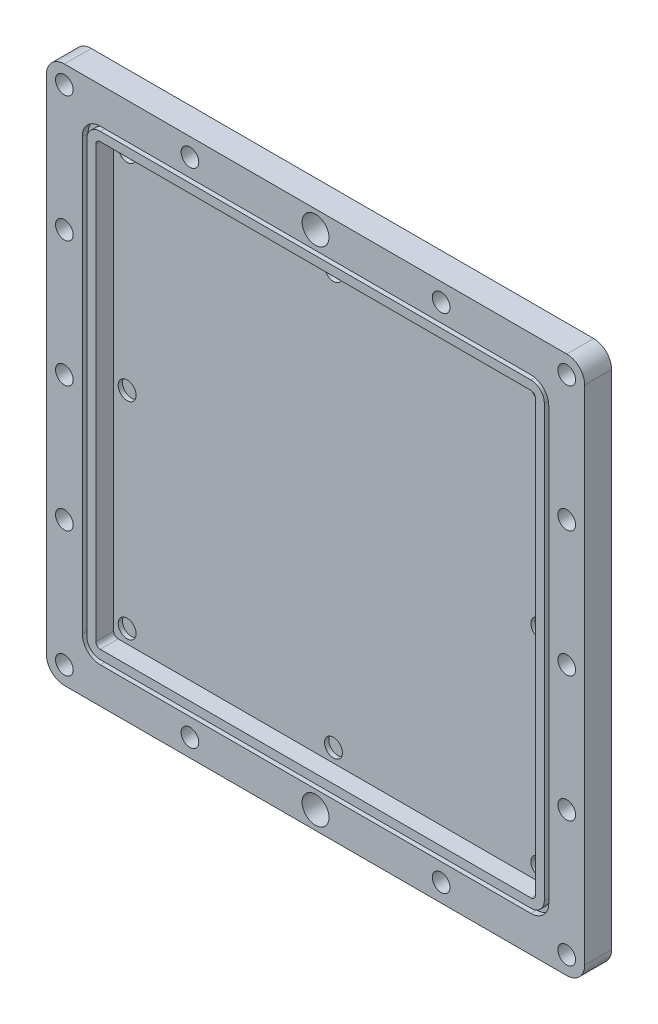
SolidWorks part; units mm, degrees
ref_plane "Front Plane" through (0, 0, 0) normal (0, 0, 1) x (1, 0, 0)
ref_plane "Top Plane" through (0, 0, 0) normal (0, 1, 0) x (1, 0, 0)
ref_plane "Right Plane" through (0, 0, 0) normal (1, 0, 0) x (0, 0, -1)
sketch "Sketch1" plane through (0, 0, 0) normal (0, 0, 1) x (1, 0, 0)
  line L1 (0, 0) -> (190.5, 0)
  line L2 (0, 0) -> (0, 190.5)
  line L3 (0, 190.5) -> (190.5, 190.5)
  line L4 (190.5, 0) -> (190.5, 190.5)
  dimension "D1" = 190.5
  dimension "D2" = 190.5
extrude "Boss-Extrude1" add sketch "Sketch1" along normal blind 9.525
sketch "Sketch4" plane through (0, 0, 9.525) normal (0, 0, 1) x (1, 0, 0)
  line L3 (0, 190.5) -> (0, 0) construction
  line L4 (6.35, 184.15) -> (184.15, 184.15) construction
  line L5 (6.35, 184.15) -> (6.35, 6.35) construction
  line L6 (6.35, 6.35) -> (184.15, 6.35) construction
  line L7 (184.15, 184.15) -> (184.15, 6.35) construction
  line L8 (190.5, 190.5) -> (0, 190.5) construction
  line L9 (190.5, 0) -> (190.5, 190.5) construction
  line L10 (0, 0) -> (190.5, 0) construction
  circle A0 centre (6.35, 6.35) radius 3.1242
  circle A1 centre (6.35, 184.15) radius 3.1242
  circle A2 centre (184.15, 184.15) radius 3.1242
  circle A3 centre (184.15, 6.35) radius 3.1242
  dimension "D5" = 6.2484
  dimension "D1" = 6.35
  dimension "D2" = 6.35
  dimension "D3" = 6.35
  dimension "D4" = 6.35
extrude "Cut-Extrude1" cut sketch "Sketch4" against normal through all
sketch "Sketch5" plane through (0, 0, 9.525) normal (0, 0, 1) x (1, 0, 0)
  line L0 (0, 190.5) -> (0, 0) construction
  line L1 (19.05, 177.8) -> (171.45, 177.8)
  line L2 (12.7, 171.45) -> (12.7, 19.05)
  line L3 (19.05, 12.7) -> (171.45, 12.7)
  line L4 (177.8, 171.45) -> (177.8, 19.05)
  line L5 (190.5, 190.5) -> (0, 190.5) construction
  line L6 (190.5, 0) -> (190.5, 190.5) construction
  line L7 (0, 0) -> (190.5, 0) construction
  line L8 (19.05, 14.2875) -> (171.45, 14.2875)
  line L9 (14.2875, 171.45) -> (14.2875, 19.05)
  line L10 (19.05, 176.2125) -> (171.45, 176.2125)
  line L11 (176.2125, 171.45) -> (176.2125, 19.05)
  arc A0 (171.45, 12.7) -> (177.8, 19.05) centre (171.45, 19.05) ccw
  arc A1 (12.7, 19.05) -> (19.05, 12.7) centre (19.05, 19.05) ccw
  arc A2 (171.45, 177.8) -> (177.8, 171.45) centre (171.45, 171.45) cw
  arc A3 (19.05, 177.8) -> (12.7, 171.45) centre (19.05, 171.45) ccw
  arc A4 (14.2875, 19.05) -> (19.05, 14.2875) centre (19.05, 19.05) ccw
  arc A5 (19.05, 176.2125) -> (14.2875, 171.45) centre (19.05, 171.45) ccw
  arc A6 (171.45, 176.2125) -> (176.2125, 171.45) centre (171.45, 171.45) cw
  arc A7 (171.45, 14.2875) -> (176.2125, 19.05) centre (171.45, 19.05) ccw
  dimension "D5" = 6.35
  dimension "D1" = 12.7
  dimension "D2" = 12.7
  dimension "D3" = 12.7
  dimension "D4" = 12.7
  dimension "D6" = 1.5875
  dimension "D7" = 1.5875
extrude "Cut-Extrude2" cut sketch "Sketch5" against normal blind 2.032 contours L1 A3 L2 A1 L3 A0 L4 A2 A7 L8 A4 L9 A5 L10 A6 L11
sketch "Sketch6" plane through (0, 0, 9.525) normal (0, 0, 1) x (1, 0, 0)
  line L8 (173.0375, 19.05) -> (173.0375, 171.45)
  line L9 (171.45, 173.0375) -> (19.05, 173.0375)
  line L10 (17.4625, 171.45) -> (17.4625, 19.05)
  line L11 (19.05, 17.4625) -> (171.45, 17.4625)
  line L12 (173.0375, 19.05) -> (173.0375, 171.45)
  line L13 (171.45, 173.0375) -> (19.05, 173.0375)
  line L14 (17.4625, 171.45) -> (17.4625, 19.05)
  line L15 (19.05, 17.4625) -> (171.45, 17.4625)
  arc A8 (171.45, 17.4625) -> (173.0375, 19.05) centre (171.45, 19.05) ccw
  arc A9 (173.0375, 171.45) -> (171.45, 173.0375) centre (171.45, 171.45) ccw
  arc A10 (19.05, 173.0375) -> (17.4625, 171.45) centre (19.05, 171.45) ccw
  arc A11 (17.4625, 19.05) -> (19.05, 17.4625) centre (19.05, 19.05) ccw
  arc A12 (171.45, 17.4625) -> (173.0375, 19.05) centre (171.45, 19.05) ccw
  arc A13 (173.0375, 171.45) -> (171.45, 173.0375) centre (171.45, 171.45) ccw
  arc A14 (19.05, 173.0375) -> (17.4625, 171.45) centre (19.05, 171.45) ccw
  arc A15 (17.4625, 19.05) -> (19.05, 17.4625) centre (19.05, 19.05) ccw
  dimension "D1" = 3.175
extrude "Cut-Extrude3" cut sketch "Sketch6" against normal blind 6.35
sketch "Sketch7" plane through (0, 0, 3.175) normal (0, 0, 1) x (1, 0, 0)
  line L0 (171.45, 173.0375) -> (19.05, 173.0375) construction
  line L1 (22.225, 168.275) -> (168.275, 168.275) construction
  line L2 (22.225, 168.275) -> (22.225, 22.225) construction
  line L3 (22.225, 22.225) -> (168.275, 22.225) construction
  line L4 (168.275, 168.275) -> (168.275, 22.225) construction
  line L5 (17.4625, 171.45) -> (17.4625, 19.05) construction
  line L6 (173.0375, 19.05) -> (173.0375, 171.45) construction
  line L7 (19.05, 17.4625) -> (171.45, 17.4625) construction
  circle A0 centre (22.225, 168.275) radius 3.175
  circle A1 centre (168.275, 168.275) radius 3.175
  circle A2 centre (22.225, 22.225) radius 3.175
  circle A3 centre (168.275, 22.225) radius 3.175
  circle A4 centre (95.25, 168.275) radius 3.175
  circle A5 centre (22.225, 95.25) radius 3.175
  circle A6 centre (168.275, 95.25) radius 3.175
  circle A7 centre (95.25, 22.225) radius 3.175
  dimension "D5" = 6.35
  dimension "D1" = 4.7625
  dimension "D2" = 4.7625
  dimension "D3" = 4.7625
  dimension "D4" = 4.7625
extrude "Cut-Extrude4" cut sketch "Sketch7" against normal blind 1.524
pattern_linear "LPattern1" count 4 spacing 44.45 along (0, -1, 0) of "Cut-Extrude1"
pattern_linear "LPattern2" count 4 spacing 44.45 along (1, 0, 0) of "Cut-Extrude1"
sketch "Sketch8" plane through (0, 0, 9.525) normal (0, 0, 1) x (1, 0, 0)
  circle A0 centre (95.25, 184.15) radius 4.7625
  circle A1 centre (95.25, 6.35) radius 4.7625
  circle A2 centre (95.25, 184.15) radius 3.1242 construction
  circle A3 centre (95.25, 6.35) radius 3.1242 construction
  dimension "D1" = 9.525
extrude "Cut-Extrude5" cut sketch "Sketch8" against normal through all
fillet "Fillet1" radius 6.35 4 edges at (190.5, 0, 4.7625) (0, 0, 4.7625) (190.5, 190.5, 4.7625) (0, 190.5, 4.7625)
